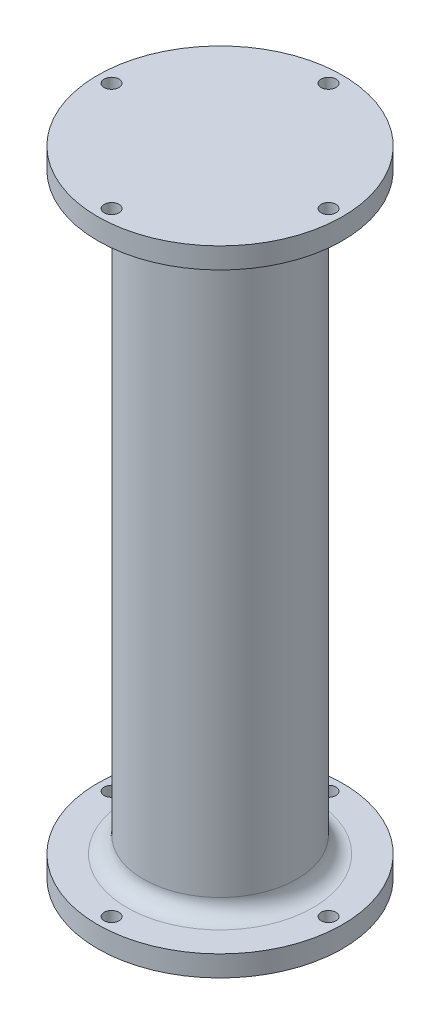
SolidWorks part; units mm, degrees
ref_plane "Front Plane" through (0, 0, 0) normal (0, 0, 1) x (1, 0, 0)
ref_plane "Top Plane" through (0, 0, 0) normal (0, 1, 0) x (1, 0, 0)
ref_plane "Right Plane" through (0, 0, 0) normal (1, 0, 0) x (0, 0, -1)
sketch "Sketch1" plane through (0, 0, 0) normal (0, 1, 0) x (1, 0, 0)
  circle A0 centre (0, 0) radius 74.5
extrude "Boss-Extrude1" add sketch "Sketch1" along normal blind 385.699
sketch "Sketch2" plane through (0, 0, 0) normal (0, 0, 1) x (1, 0, 0)
  line L2 (-74.5, 385.699) -> (-74.5, 0) construction
  line L5 (-74.5, 372.999) -> (-46.6422, 372.999)
  line L6 (-74.5, 372.999) -> (-74.5, 12.7)
  line L7 (-74.5, 12.7) -> (-46.6422, 12.7)
  line L8 (-46.6422, 372.999) -> (-46.6422, 12.7)
revolve "Cut-Revolve4" cut sketch "Sketch2" angle 360 about axis through (0, 385.699, 0) along (0, -1, 0)
sketch "Sketch3" plane through (0, 0, 0) normal (0, -1, 0) x (1, 0, 0)
  circle A0 centre (0, 66.0001) radius 4.5
  dimension "D1" = 66.0001
extrude "Cut-Extrude1" cut sketch "Sketch3" against normal through all
pattern_circular "CirPattern1" count 4 every 90 about axis through (0, 0, 0) along (0, 1, 0) of "Cut-Extrude1"
fillet "Fillet1" radius 10 2 edges at (0, 12.7, 46.6422) (0, 372.999, 46.6422)
sketch3d "3DSketch1" plane through (0, 0, 0) normal (0, 0, 1) x (1, 0, 0)
  dimension "D1" = 74.5
